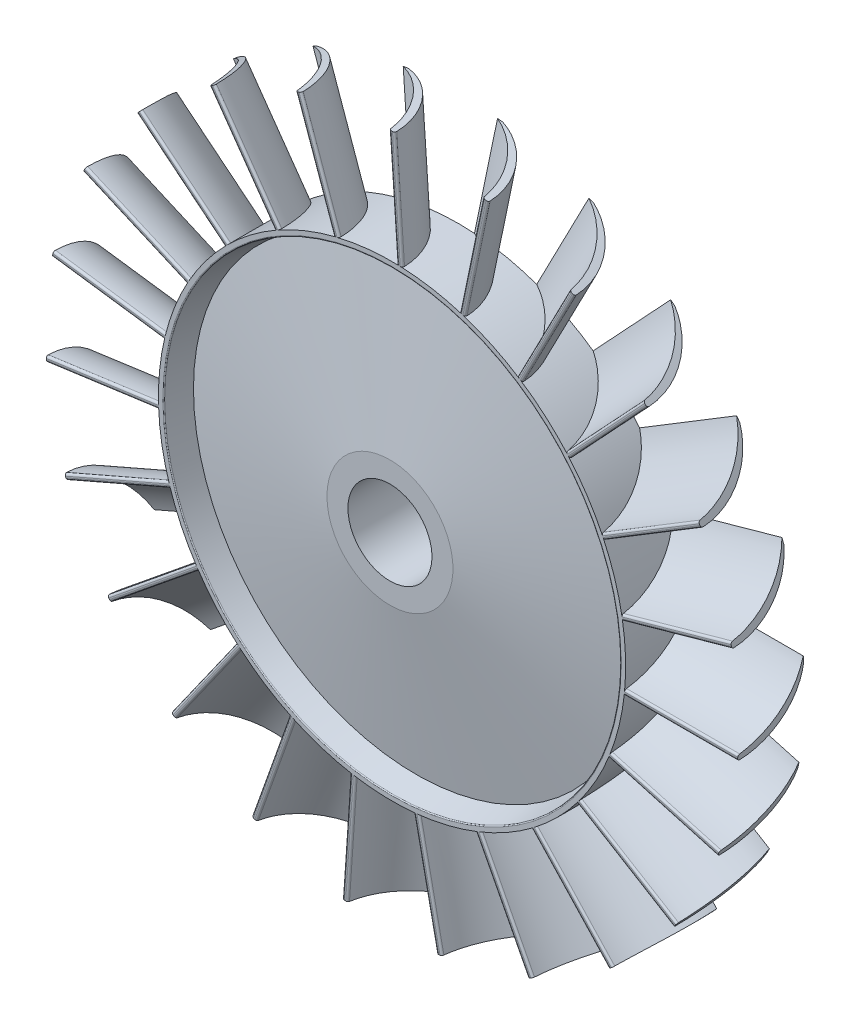
SolidWorks part; units mm, degrees
material "Nickel"
ref_plane "Front Plane" through (0, 0, 0) normal (0, 0, 1) x (1, 0, 0)
ref_plane "Top Plane" through (0, 0, 0) normal (0, 1, 0) x (1, 0, 0)
ref_plane "Right Plane" through (0, 0, 0) normal (1, 0, 0) x (0, 0, -1)
sketch "Sketch1" plane through (0, 0, 0) normal (0, 1, 0) x (1, 0, 0)
  line L0 (-4, 3.35) -> (-4, -3.35)
  line L1 (-4, -3.35) -> (-6, -3.35)
  line L2 (-22.25, 3.15) -> (-22.25, -3.15)
  line L3 (0, 0) -> (0, -2.4212) construction
  line L4 (-22.25, -3.15) -> (-21.75, -3.15)
  line L5 (-21.75, -3.15) -> (-21.2057, -0.858)
  line L6 (-21.2057, -0.858) -> (-6, -3.35)
  line L7 (-4, 3.35) -> (-6, 3.35)
  line L8 (-21.2057, 0.858) -> (-6, 3.35)
  line L9 (-22.25, 3.15) -> (-21.75, 3.15)
  line L10 (-21.75, 3.15) -> (-21.2057, 0.858)
revolve "Revolve1" add sketch "Sketch1" angle 360 about L3
fillet "Fillet3" radius 0.1 1 edges at (-21.75, 0, -3.15)
fillet "Fillet4" radius 0.1 1 edges at (-21.75, 0, 3.15)
ref_plane "Plane1" through (22, 0, 0) normal (1, 0, 0) x (0, 0, -1)
sketch "Sketch2" plane through (22, 0, 0) normal (1, 0, 0) x (0, 0, -1)
  line L1 (-3.15, 22.25) -> (-3.15, -22.25) construction
  line L3 (3.15, -22.25) -> (3.15, 22.25) construction
  line L4 (-3.15, -2.2965) -> (-3.15, -2.1746)
  line L5 (3.15, 2.5) -> (3.15, 3)
  arc A0 (-2.9433, -2.4964) -> (3.15, 2.5) centre (-3.1607, 3.9824) ccw
  arc A1 (-2.9792, -1.9767) -> (3.15, 3) centre (-4.1109, 5.6797) ccw
  arc A2 (-3.15, -2.1746) -> (-2.9792, -1.9767) centre (-2.95, -2.1746) cw
  arc A3 (-2.9433, -2.4964) -> (-3.15, -2.2965) centre (-2.95, -2.2965) cw
  point P14 (-3.15, -2.5)
  dimension "D1" = 0.2
  dimension "D2" = 0.2
extrude "Boss-Extrude1" add sketch "Sketch2" along normal blind 11
pattern_circular "CirPattern1" count 23 over 360 about axis through (0, 0, 0) along (0, 0, 1) of "Boss-Extrude1"
sketch "Sketch3" plane through (0, 0, 3.35) normal (0, 0, 1) x (1, 0, 0)
  circle A0 centre (0, 0) radius 33
  circle A1 centre (0, 0) radius 34
extrude "Cut-Extrude1" cut sketch "Sketch3" against normal blind 11.5
